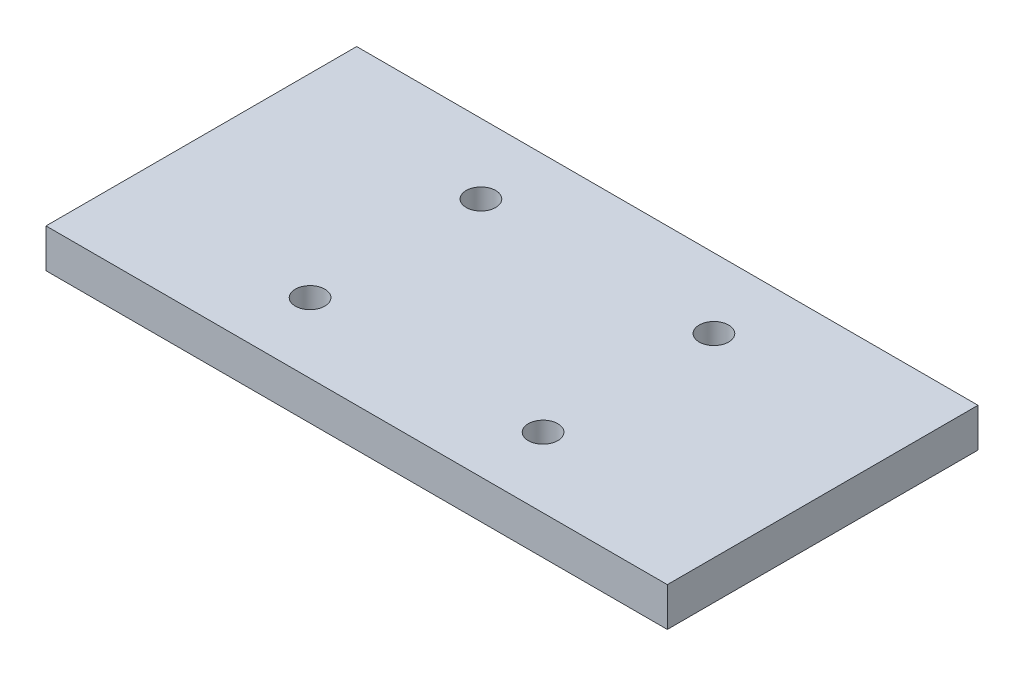
SolidWorks part; units mm, degrees
ref_plane "Front Plane" through (0, 0, 0) normal (0, 0, 1) x (1, 0, 0)
ref_plane "Top Plane" through (0, 0, 0) normal (0, 1, 0) x (1, 0, 0)
ref_plane "Right Plane" through (0, 0, 0) normal (1, 0, 0) x (0, 0, -1)
sketch "Sketch1" plane through (0, 0, 0) normal (0, 1, 0) x (1, 0, 0)
  line L1 (-50.8, -25.4) -> (50.8, -25.4)
  line L2 (-50.8, -25.4) -> (-50.8, 25.4)
  line L3 (-50.8, 25.4) -> (50.8, 25.4)
  line L4 (50.8, -25.4) -> (50.8, 25.4)
  line L5 (-50.8, -25.4) -> (50.8, 25.4) construction
  line L6 (-50.8, 25.4) -> (50.8, -25.4) construction
  point P0 (0, 0)
  dimension "D1" = 101.6
  dimension "D2" = 50.8
extrude "Boss-Extrude1" add sketch "Sketch1" along normal blind 6.35
hole_wizard "CSK for #10 Flat Head Machine Screw1" positions "Sketch3" profile "Sketch4" countersink size "#10" standard "ANSI Inch" end condition through all
sketch "Sketch3" plane through (0, 0, 0) normal (0, -1, 0) x (-1, 0, 0)
  line L0 (50.8, -25.4) -> (-50.8, -25.4) construction
  line L2 (50.8, 25.4) -> (50.8, -25.4) construction
  line L4 (0, -17.8498) -> (0, 0) construction
  line L5 (0, 0) -> (-17.2096, 0) construction
  point P0 (19.05, -13.97)
  point P24 (-19.05, -13.97)
  point P25 (-19.05, 13.97)
  point P26 (19.05, 13.97)
  dimension "D1" = 11.43
  dimension "D2" = 31.75
sketch "Sketch4" plane through (-19.05, 0, 13.97) normal (1, 0, 0) x (0, 0, -1)
  line L0 (0, 0) -> (0, 6.35)
  line L1 (0, 6.35) -> (2.413, 6.35)
  line L2 (2.413, 6.35) -> (2.413, 2.7028)
  line L3 (2.413, 2.7028) -> (4.7625, 0)
  line L5 (4.7625, 0) -> (0, 0)
  line L6 (-2.413, 2.7028) -> (-4.7625, 0) construction
  line L11 (0, -6.35) -> (0, 107.95) construction
  dimension "Thru Hole Dia." = 4.826
  dimension "Thru Hole Depth" = 6.35
  dimension "Near C'Sink Dia." = 9.525
  dimension "Near C'Sink Angle" = 82
